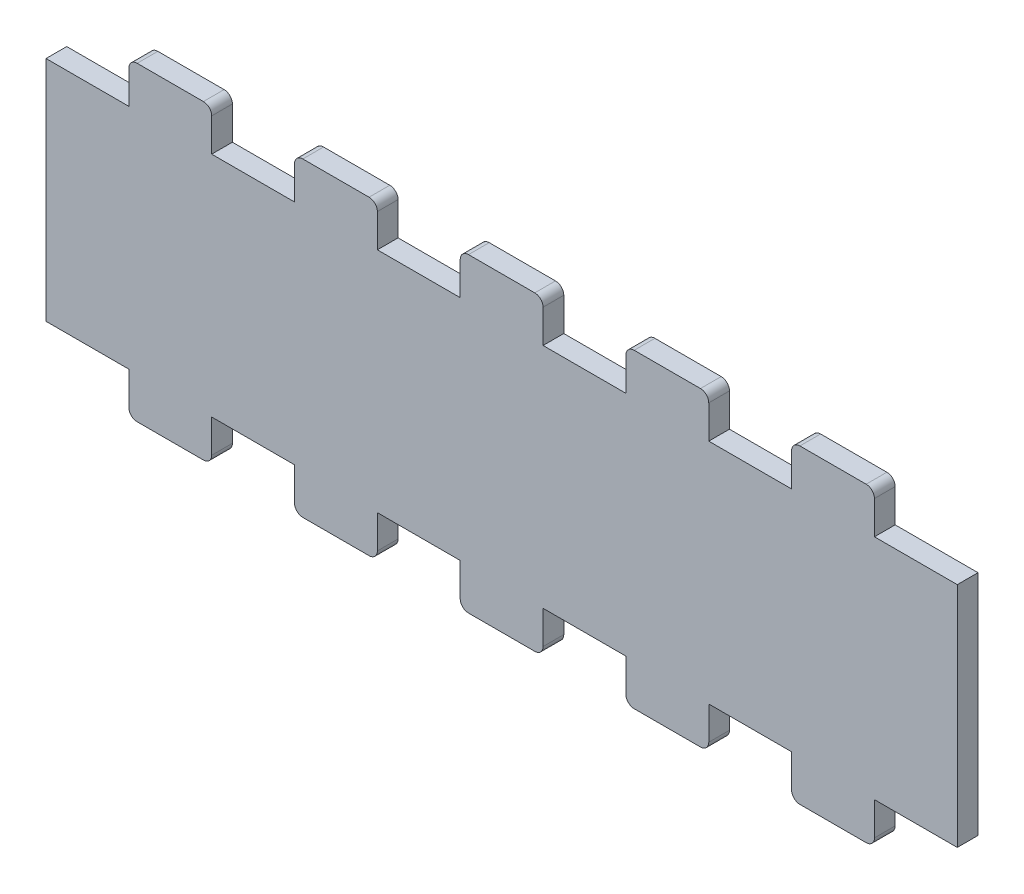
SolidWorks part; units mm, degrees
ref_plane "Front" through (0, 0, 0) normal (0, 0, 1) x (1, 0, 0)
ref_plane "Top" through (0, 0, 0) normal (0, 1, 0) x (1, 0, 0)
ref_plane "Right" through (0, 0, 0) normal (1, 0, 0) x (0, 0, -1)
sketch "Sketch1" plane through (0, 0, 0) normal (0, 0, 1) x (1, 0, 0)
  line L1 (0, 0) -> (220, 0)
  line L2 (0, 0) -> (0, 54.95)
  line L3 (0, 54.95) -> (220, 54.95)
  line L4 (220, 0) -> (220, 54.95)
  dimension "D1" = 54.95
  dimension "D2" = 220
extrude "Boss-Extrude1" add sketch "Sketch1" along normal blind 5
sketch "Sketch2" plane through (0, 0, 5) normal (0, 0, 1) x (1, 0, 0)
  line L0 (220, 54.95) -> (0, 54.95) construction
  line L1 (20, 54.95) -> (40, 54.95)
  line L2 (20, 54.95) -> (20, 64.95)
  line L3 (20, 64.95) -> (40, 64.95)
  line L4 (40, 54.95) -> (40, 64.95)
  line L5 (0, 54.95) -> (0, 0) construction
  line L6 (60, 54.95) -> (60, 64.95)
  line L7 (60, 54.95) -> (80, 54.95)
  line L8 (80, 54.95) -> (80, 64.95)
  line L9 (60, 64.95) -> (80, 64.95)
  line L10 (100, 54.95) -> (100, 64.95)
  line L11 (100, 54.95) -> (120, 54.95)
  line L12 (120, 54.95) -> (120, 64.95)
  line L13 (100, 64.95) -> (120, 64.95)
  line L14 (140, 54.95) -> (140, 64.95)
  line L15 (140, 54.95) -> (160, 54.95)
  line L16 (160, 54.95) -> (160, 64.95)
  line L17 (140, 64.95) -> (160, 64.95)
  line L18 (180, 54.95) -> (180, 64.95)
  line L19 (180, 54.95) -> (200, 54.95)
  line L20 (200, 54.95) -> (200, 64.95)
  line L21 (180, 64.95) -> (200, 64.95)
  dimension "D1" = 20
  dimension "D2" = 10
  dimension "D3" = 20
  dimension "D4" = 5
extrude "Boss-Extrude2" add sketch "Sketch2" against normal up to surface (5 mm away) up to face at (110, 27.475, 0)
ref_plane "Plane1" through (0, 27.475, 0) normal (0, 1, 0) x (1, 0, 0)
fillet "Fillet1" radius 2 10 edges at (200, 64.95, 2.5) (180, 64.95, 2.5) (140, 64.95, 2.5) (160, 64.95, 2.5) (120, 64.95, 2.5) (100, 64.95, 2.5) (80, 64.95, 2.5) (60, 64.95, 2.5) (40, 64.95, 2.5) (20, 64.95, 2.5)
mirror "Mirror1" about plane through (0, 27.475, 0) normal (0, 1, 0) of "Fillet1", "Boss-Extrude2"
